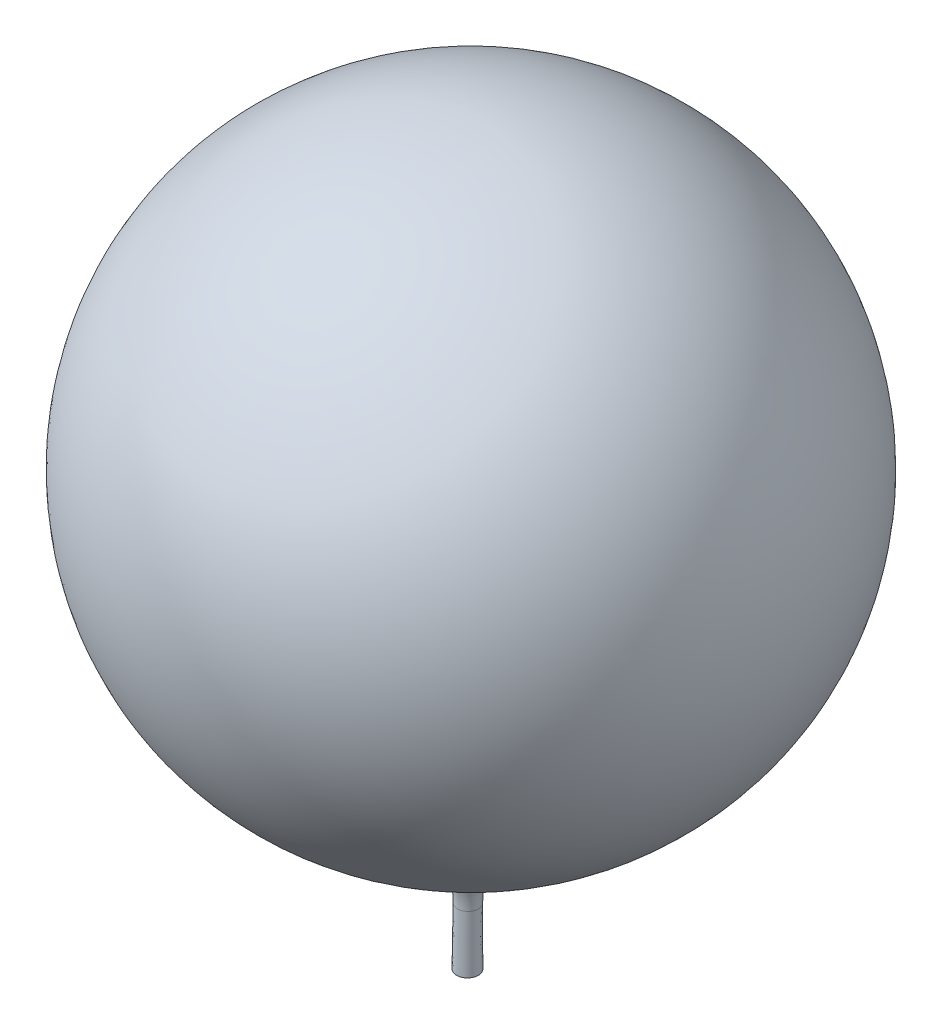
SolidWorks part; units mm, degrees
ref_plane "Front Plane" through (0, 0, 0) normal (0, 0, 1) x (1, 0, 0)
ref_plane "Top Plane" through (0, 0, 0) normal (0, 1, 0) x (1, 0, 0)
ref_plane "Right Plane" through (0, 0, 0) normal (1, 0, 0) x (0, 0, -1)
sketch "Sketch1" plane through (0, 0, 0) normal (0, 0, 1) x (1, 0, 0)
  line L0 (0, 995.4471) -> (0, -1557.7297) construction
  line L1 (0, 914.4) -> (-15, -914.277)
  line L2 (15, -914.277) -> (15, -1334)
  line L3 (15, -1334) -> (-15, -1334)
  line L4 (-15, -914.277) -> (-15, -1334)
  line L5 (9.7826, -914.3477) -> (-15, -1334) construction
  line L6 (15, -1334) -> (0, -1080) construction
  arc A0 (15, -914.277) -> (0, 914.4) centre (0, 0) ccw
  point P2 (0, -1080)
  dimension "D1" = 1828.8
  dimension "D2" = 30
  dimension "D3" = 1080
  dimension "D4" = 0
revolve "Revolve1" add sketch "Sketch1" angle 360 about L1
fillet "Fillet1" radius 280 1 edges at (-44.996, -913.7848, 0)
